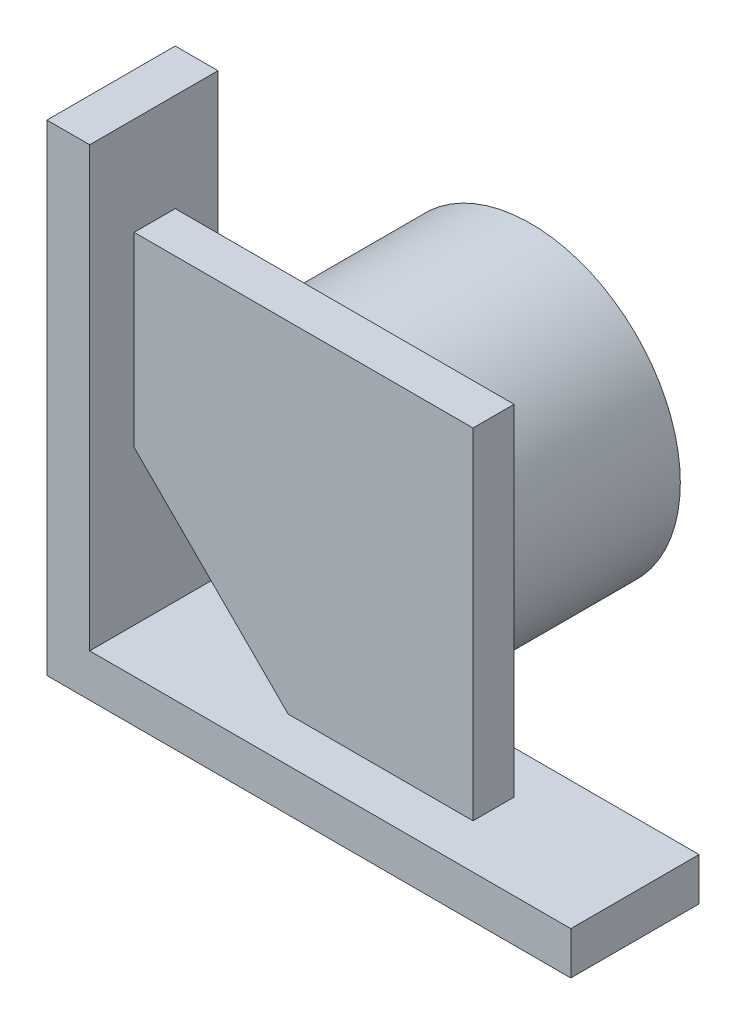
SolidWorks part; units mm, degrees
ref_plane "Front Plane" through (0, 0, 0) normal (0, 0, 1) x (1, 0, 0)
ref_plane "Top Plane" through (0, 0, 0) normal (0, 1, 0) x (1, 0, 0)
ref_plane "Right Plane" through (0, 0, 0) normal (1, 0, 0) x (0, 0, -1)
sketch "Sketch1" plane through (0, 0, 0) normal (-1, 0, 0) x (0, -1, 0)
  line L0 (0, -76.659) -> (0, 176.2699) construction
  line L1 (-45.4446, 0) -> (105.5783, 0) construction
  line L3 (0, 0) -> (-12.7, 0)
  line L4 (0, 0) -> (0, 38.1)
  line L5 (0, 38.1) -> (-12.7, 38.1)
  line L6 (-12.7, 0) -> (-12.7, 38.1)
  dimension "D1" = 38.1
  dimension "D2" = 12.7
extrude "Boss-Extrude1" add sketch "Sketch1" against normal blind 155.575
sketch "Sketch3" plane through (0, 12.7, 0) normal (0, 1, 0) x (1, 0, 0)
  line L0 (155.575, -38.1) -> (0, -38.1) construction
  line L1 (0, 0) -> (12.7, 0)
  line L2 (0, 0) -> (0, -38.1)
  line L3 (0, -38.1) -> (12.7, -38.1)
  line L4 (12.7, 0) -> (12.7, -38.1)
  dimension "D1" = 12.7
extrude "Boss-Extrude2" add sketch "Sketch3" along normal blind 130.175
sketch "Sketch4" plane through (0, 12.7, 0) normal (0, 1, 0) x (1, 0, 0)
  line L0 (12.7, -38.1) -> (12.7, 0) construction
  line L1 (12.7, -12.7) -> (113.3348, -12.7)
  line L2 (12.7, -12.7) -> (12.7, -24.892)
  line L3 (12.7, -24.892) -> (113.3348, -24.892)
  line L4 (113.3348, -12.7) -> (113.3348, -24.892)
  dimension "D1" = 100.6348
  dimension "D2" = 12.192
  dimension "D3" = 12.7
extrude "Boss-Extrude3" add sketch "Sketch4" along normal blind 101.0412
sketch "Sketch5" plane through (0, 0, 24.892) normal (0, 0, 1) x (1, 0, 0)
  line L0 (12.7, 58.42) -> (58.42, 12.7)
  line L1 (12.7, 113.7412) -> (12.7, 12.7) construction
  line L2 (155.575, 12.7) -> (12.7, 12.7) construction
  line L3 (58.42, 12.7) -> (12.7, 12.7)
  line L4 (12.7, 12.7) -> (12.7, 58.42)
  point P6 (0, 0)
  point P10 (12.9269, 53.0564)
  dimension "D1" = 45.72
  dimension "D2" = 45.72
sketch "Sketch7" plane through (0, 0, 0) normal (0, 1, 0) x (1, 0, 0)
  line L0 (0, 66.6649) -> (0, -63.5607) construction
  line L1 (-10.7252, 48.3616) -> (133.7438, 48.3616) construction
  line L2 (113.3348, -12.7) -> (12.7, -12.7) construction
  dimension "D1" = 61.0616
sketch "Sketch6" plane through (0, 0, 12.7) normal (0, 0, -1) x (-1, 0, 0)
  line L3 (-57.2008, 61.6364) -> (-57.2008, 4.9884) construction
  line L4 (-61.9953, 57.2008) -> (-4.3021, 57.2008) construction
  line L5 (-113.3348, 12.7) -> (-12.7, 12.7) construction
  line L6 (-12.7, 12.7) -> (-12.7, 58.42) construction
  circle A0 centre (-57.2008, 57.2008) radius 44.45
  circle A1 centre (-57.2008, 57.2008) radius 39.3192
  point P8 (-12.7508, 57.2008)
  point P9 (-57.2008, 12.7508)
  dimension "D1" = 88.9
  dimension "D3" = 0.0508
  dimension "D4" = 0.0508
  dimension "D2" = 5.1308
ref_plane "Plane1" through (0, 0, -48.3616) normal (0, 0, 1) x (1, 0, 0)
extrude "Cut-Extrude2" cut sketch "Sketch5" against normal up to surface (12.192 mm away) up to face at (63.0174, 63.2206, 12.7)
extrude "Boss-Extrude8" add sketch "Sketch6" against normal up to surface (61.0616 mm away) from surface at 61.0616 contours A0 A1 up to face at (62.0979, 62.2605, 12.7) starting at plane "Plane1"
